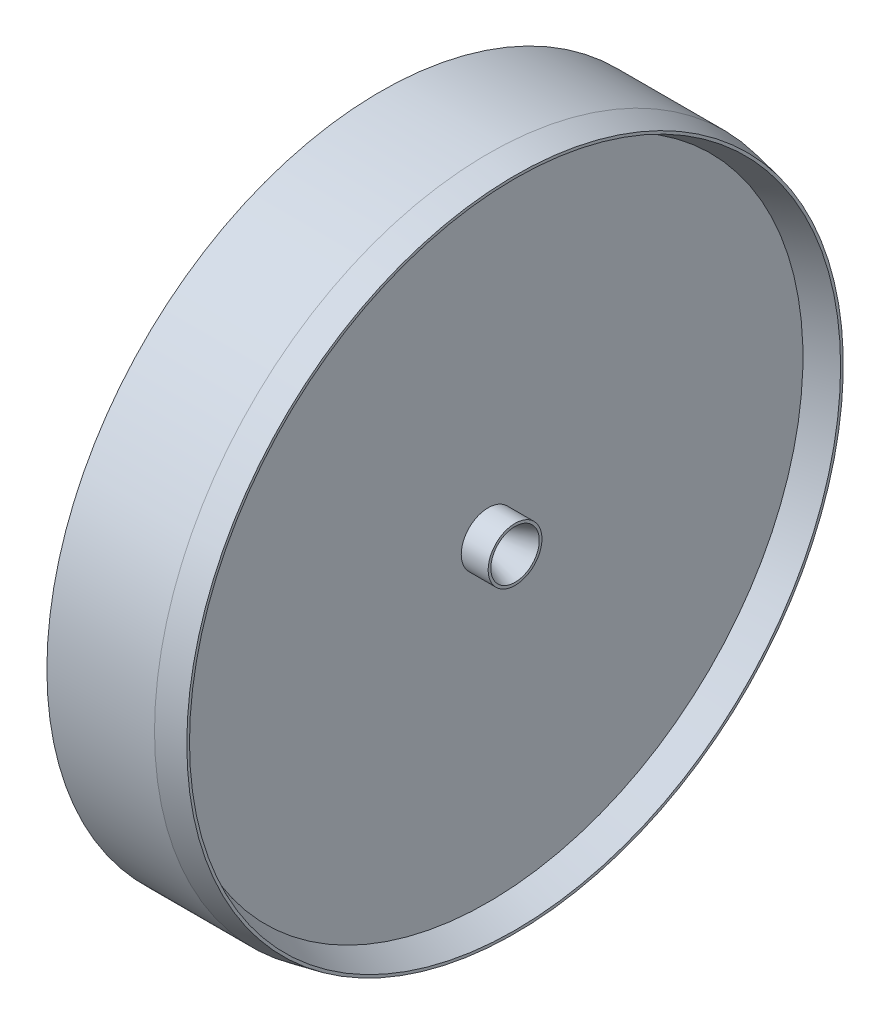
SolidWorks part; units mm, degrees
ref_plane "Płaszczyzna przednia" through (0, 0, 0) normal (0, 0, 1) x (1, 0, 0)
ref_plane "Płaszczyzna górna" through (0, 0, 0) normal (0, 1, 0) x (1, 0, 0)
ref_plane "Płaszczyzna prawa" through (0, 0, 0) normal (1, 0, 0) x (0, 0, -1)
sketch "Szkic1" plane through (0, 0, 0) normal (0, 0, 1) x (1, 0, 0)
  line L0 (0, 12.4) -> (0, 0)
  line L1 (0, 0) -> (4, 0)
  line L2 (4, 0) -> (4, 0.5)
  line L3 (4, 0.5) -> (5, 0.9)
  line L4 (5, 0.9) -> (5, 1)
  line L5 (5, 1) -> (4, 1)
  line L6 (4, 1) -> (4, 11.7)
  line L7 (4, 11.7) -> (5, 12.1)
  line L8 (5, 12.1) -> (5, 12.2)
  line L9 (5, 12.2) -> (4, 12.4)
  line L10 (4, 12.4) -> (0, 12.4)
  point P0 (20, 11.7868)
  point P9 (0, 38.9382)
  dimension "D1" = 12.4
  dimension "D2" = 4
  dimension "D3" = 1
  dimension "D4" = 0.1
  dimension "D5" = 12.2
  dimension "D6" = 1
  dimension "D7" = 0.5
revolve "Obrót1" add sketch "Szkic1" angle 360 about L1
